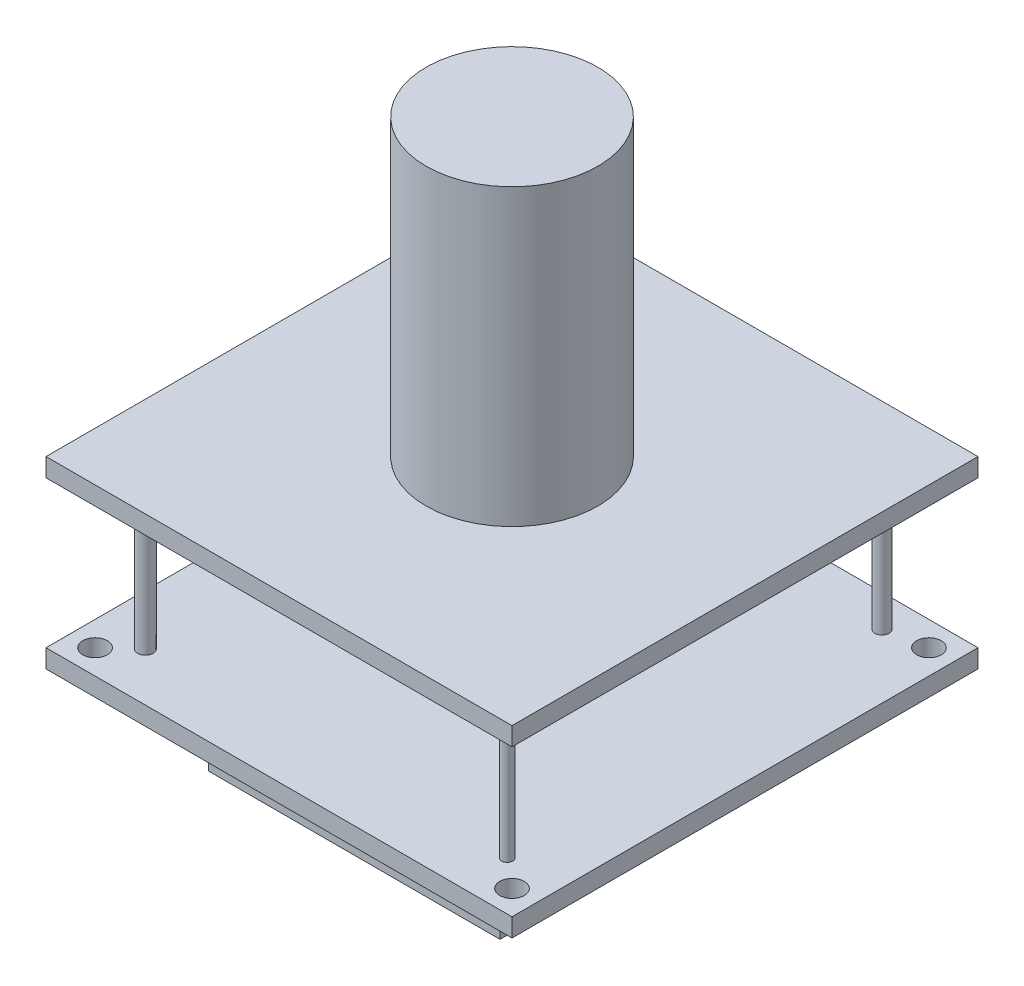
SolidWorks part; units mm, degrees
ref_plane "前视基准面" through (0, 0, 0) normal (0, 0, 1) x (1, 0, 0)
ref_plane "上视基准面" through (0, 0, 0) normal (0, 1, 0) x (1, 0, 0)
ref_plane "右视基准面" through (0, 0, 0) normal (1, 0, 0) x (0, 0, -1)
other "Configuration Table"
sketch "草图1" plane through (0, 0, 0) normal (0, 1, 0) x (1, 0, 0)
  line L1 (0, 0) -> (38, 0)
  line L2 (0, 0) -> (0, -38)
  line L3 (0, -38) -> (38, -38)
  line L4 (38, 0) -> (38, -38)
  circle A0 centre (2, -2) radius 1
  circle A1 centre (36, -2) radius 1
  circle A2 centre (36, -36) radius 1
  circle A3 centre (2, -36) radius 1
  dimension "D3" = 2
  dimension "D4" = 2
  dimension "D5" = 2
  dimension "D1" = 38
  dimension "D2" = 38
  dimension "D6" = 2
  dimension "D7" = 2
extrude "凸台-拉伸1" add sketch "草图1" along normal blind 1.5
sketch "草图2" plane through (0, 1.5, 0) normal (0, 1, 0) x (1, 0, 0)
  circle A0 centre (4.1285, -34.0307) radius 0.6367
  circle A1 centre (4.7652, -3.0597) radius 0.4479
  circle A2 centre (32.78, -2.6118) radius 0.5771
  circle A3 centre (33.6441, -34.0307) radius 0.4548
extrude "凸台-拉伸2" add sketch "草图2" along normal blind 12
sketch "草图3" plane through (0, 13.5, 0) normal (0, 1, 0) x (1, 0, 0)
  line L1 (0, 0) -> (38, 0)
  line L2 (0, 0) -> (0, -38)
  line L3 (0, -38) -> (38, -38)
  line L4 (38, 0) -> (38, -38)
extrude "凸台-拉伸3" add sketch "草图3" along normal blind 1.5
sketch "草图4" plane through (0, 15, 0) normal (0, 1, 0) x (1, 0, 0)
  circle A0 centre (19, -19) radius 7
  dimension "D1" = 14
extrude "凸台-拉伸4" add sketch "草图4" along normal blind 24
sketch "草图5" plane through (0, 0, 0) normal (0, -1, 0) x (-1, 0, 0)
  line L0 (-38, 0) -> (0, 0) construction
  line L1 (-7.221, -31.9842) -> (-31.0064, -31.9842)
  line L2 (-7.221, -31.9842) -> (-7.221, -7.1528)
  line L3 (-7.221, -7.1528) -> (-31.0064, -7.1528)
  line L4 (-31.0064, -31.9842) -> (-31.0064, -7.1528)
  line L5 (-15.1798, 0) -> (-22.4564, 0)
  line L6 (-15.1798, 0) -> (-15.1798, -1.9228)
  line L7 (-15.1798, -1.9228) -> (-22.4564, -1.9228)
  line L8 (-22.4564, 0) -> (-22.4564, -1.9228)
extrude "凸台-拉伸5" add sketch "草图5" along normal blind 6.6
